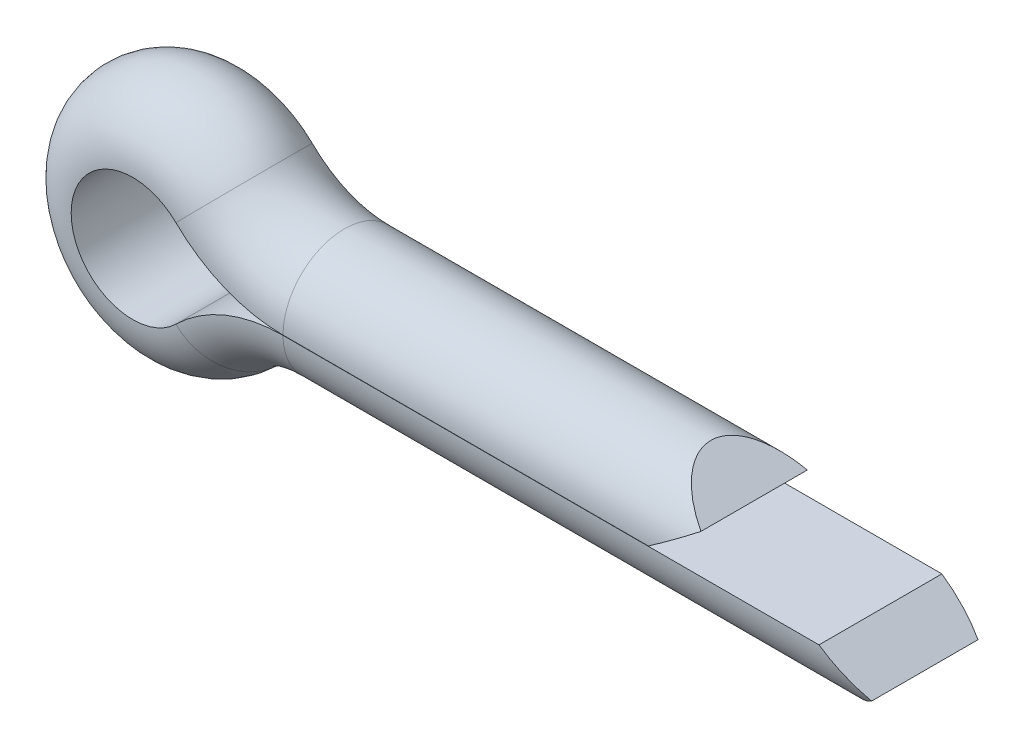
SolidWorks part; units mm, degrees
ref_plane "Front" through (0, 0, 0) normal (0, 0, 1) x (1, 0, 0)
ref_plane "Top" through (0, 0, 0) normal (0, 1, 0) x (1, 0, 0)
ref_plane "Right" through (0, 0, 0) normal (1, 0, 0) x (0, 0, -1)
sketch "PathSke" plane through (0, 0, 0) normal (0, 0, 1) x (1, 0, 0)
  line L0 (6, 0.9) -> (0, 0.9)
  line L1 (0, -0.9) -> (8.5, -0.9)
  line L2 (0, 0) -> (49.7718, 0) construction
  line L3 (0, 0) -> (0, 16.5256) construction
  line L4 (-4, 0) -> (-4, 12.0776) construction
  arc A0 (0, 0.9) -> (-0.9384, 1.2839) centre (0, 2.2389) cw
  arc A1 (-0.9384, 1.2839) -> (-0.9384, -1.2839) centre (-2.2, 0) ccw
  arc A2 (-0.9384, -1.2839) -> (0, -0.9) centre (0, -2.2389) cw
  dimension "Diameter" = 1.8
  dimension "Head_dia" = 3.6
  dimension "Head_ht" = 4
  dimension "Length" = 6
  dimension "Tip_offset" = 2.5
ref_plane "SectionPlane" through (6, 0, 0) normal (1, 0, 0) x (0, 0, -1)
sketch "SectionSke" plane through (6, 0, 0) normal (1, 0, 0) x (0, 0, -1)
  line L1 (-0.9, 0.002) -> (0.9, 0.002)
  arc A0 (0.9, 0.002) -> (-0.9, 0.002) centre (0, 0) ccw
  dimension "Diameter" = 1.8
  dimension "D1" = 0.002
sweep "Body" add profiles "SectionSke" path "PathSke"
sketch "ConeCutSke" plane through (0, 0, 0) normal (0, 0, 1) x (1, 0, 0)
  line L0 (0, 0) -> (0, 16.2682) construction
  line L1 (0, 0) -> (75.9079, 0) construction
  line L2 (0, 0) -> (8.5, 0) construction
  line L3 (6, 0.451) -> (5.353, 0.91)
  line L4 (6, 0.002) -> (6, 0.9) construction
  line L6 (6, 0.451) -> (5.3474, 0)
  line L7 (8.5, -0.451) -> (7.8474, 0)
  line L8 (8.5, -0.9) -> (8.5, -0.002) construction
  line L9 (8.5, -0.451) -> (7.853, -0.91)
  line L10 (7.8474, 0) -> (5.3474, 0)
  line L11 (5.353, 0.91) -> (8.51, 0.91)
  line L12 (8.51, 0.91) -> (8.51, -0.91)
  line L13 (8.51, -0.91) -> (7.853, -0.91)
  line L14 (6, 0.9) -> (0, 0.9) construction
  dimension "D1" = 0.01
  dimension "D2" = 0.01
  dimension "D3" = 70
  dimension "D4" = 70
extrude "ConeCut" cut sketch "ConeCutSke" against normal through all and the other way through all
equation "' \"Diameter@PathSke\" = 9.5"
equation "' \"Head_dia@PathSke\" = 19"
equation "' \"Head_ht@PathSke\" = 20"
equation "' \"Tip_offset@PathSke\" = 6.3"
equation "' \"Length@PathSke\" = 45"
equation "' \"Diameter@PathSke\" = 1"
equation "' \"Head_dia@PathSke\" = 2"
equation "' \"Head_ht@PathSke\" = 3"
equation "' \"Tip_offset@PathSke\" = 2.5"
equation "' \"Length@PathSke\" = 8"
equation "' \"Diameter@PathSke\" = 0.5"
equation "' \"Head_dia@PathSke\" = 1"
equation "' \"Head_ht@PathSke\" = 2"
equation "' \"Tip_offset@PathSke\" = 1.6"
equation "' \"Length@PathSke\" = 4"
equation "\"Diameter@SectionSke\" = \"Diameter@PathSke\""
equation "\"Length@SectionPlane\" = \"Length@PathSke\""
